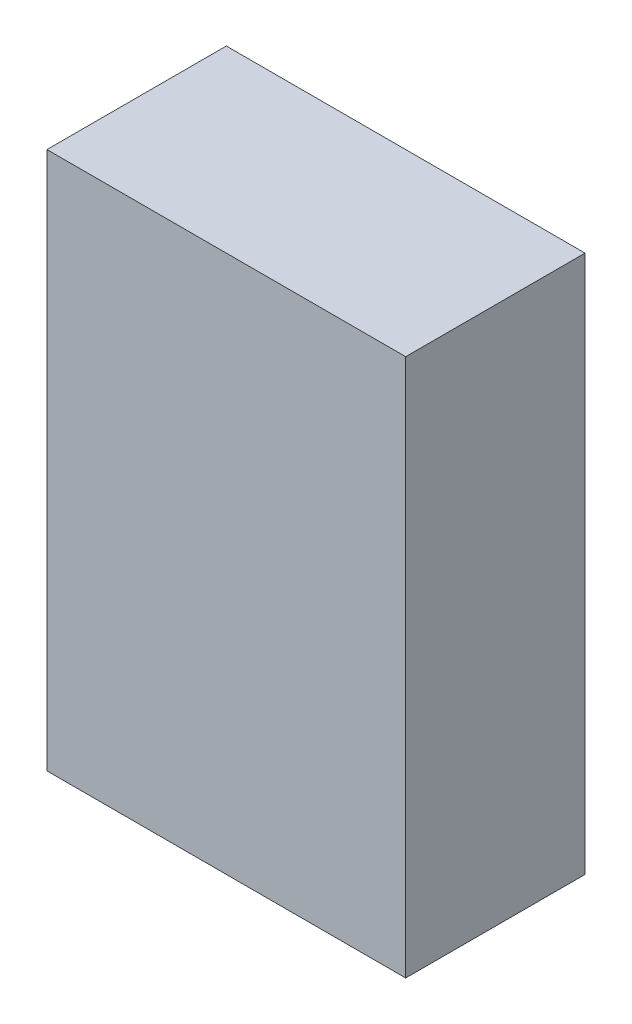
SolidWorks part; units mm, degrees
ref_plane "Ebene vorne" through (0, 0, 0) normal (0, 0, 1) x (1, 0, 0)
ref_plane "Ebene oben" through (0, 0, 0) normal (0, 1, 0) x (1, 0, 0)
ref_plane "Ebene rechts" through (0, 0, 0) normal (1, 0, 0) x (0, 0, -1)
sketch "Sketch1" plane through (0, 0, 0) normal (0, 0, 1) x (1, 0, 0)
  line L1 (-14.6333, 14.0146) -> (5.3667, 14.0146)
  line L2 (-14.6333, 14.0146) -> (-14.6333, -15.9854)
  line L3 (-14.6333, -15.9854) -> (5.3667, -15.9854)
  line L4 (5.3667, 14.0146) -> (5.3667, -15.9854)
  dimension "D1" = 30
  dimension "D2" = 20
extrude "Boss-Extrude1" add sketch "Sketch1" along normal blind 10
